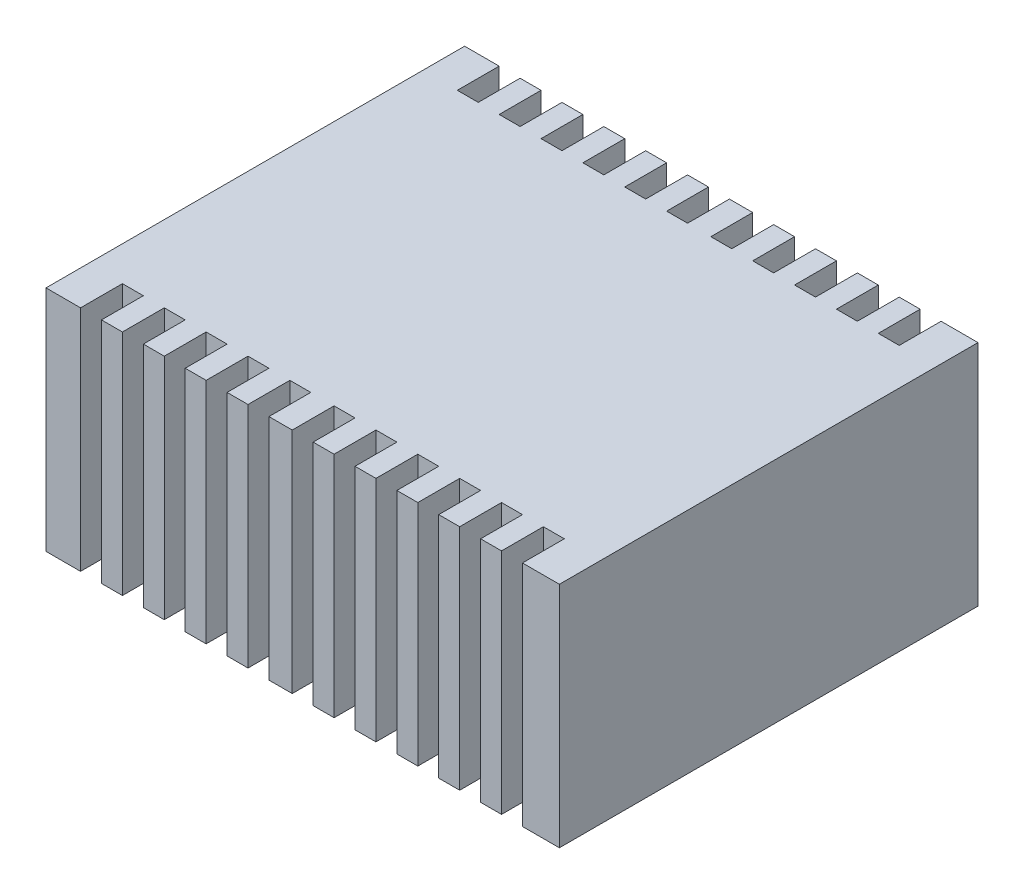
SolidWorks part; units mm, degrees
ref_plane "Front Plane" through (0, 0, 0) normal (0, 0, 1) x (1, 0, 0)
ref_plane "Top Plane" through (0, 0, 0) normal (0, 1, 0) x (1, 0, 0)
ref_plane "Right Plane" through (0, 0, 0) normal (1, 0, 0) x (0, 0, -1)
sketch "Sketch1" plane through (0, 0, 0) normal (0, 0, 1) x (1, 0, 0)
  line L0 (390.2862, -454.0022) -> (340.2862, -454.0022)
  line L1 (-347.891, 41.2406) -> (878.4633, 41.2406)
  line L2 (-347.891, 41.2406) -> (-347.891, -504.0022)
  line L3 (-347.891, -504.0022) -> (-265.3555, -504.0022)
  line L4 (878.4633, 41.2406) -> (878.4633, -504.0022)
  line L5 (340.2862, -454.0022) -> (340.2862, -504.0022)
  line L6 (290.2862, -454.0022) -> (240.2862, -454.0022)
  line L7 (240.2862, -454.0022) -> (240.2862, -504.0022)
  line L8 (290.2862, -454.0022) -> (290.2862, -504.0022)
  line L9 (390.2862, -454.0022) -> (390.2862, -504.0022)
  line L10 (490.2862, -454.0022) -> (440.2862, -454.0022)
  line L11 (440.2862, -454.0022) -> (440.2862, -504.0022)
  line L12 (490.2862, -454.0022) -> (490.2862, -504.0022)
  line L13 (590.2862, -454.0022) -> (540.2862, -454.0022)
  line L14 (540.2862, -454.0022) -> (540.2862, -504.0022)
  line L15 (690.2862, -454.0022) -> (690.2862, -504.0022)
  line L16 (590.2862, -454.0022) -> (590.2862, -504.0022)
  line L17 (690.2862, -454.0022) -> (640.2862, -454.0022)
  line L18 (640.2862, -454.0022) -> (640.2862, -504.0022)
  line L19 (184.6445, -454.0022) -> (134.6445, -454.0022)
  line L20 (790.2862, -454.0022) -> (740.2862, -454.0022)
  line L21 (740.2862, -454.0022) -> (740.2862, -504.0022)
  line L22 (-265.3555, -454.0022) -> (-265.3555, -504.0022)
  line L23 (184.6445, -454.0022) -> (184.6445, -504.0022)
  line L24 (790.2862, -454.0022) -> (790.2862, -504.0022)
  line L25 (84.6445, -454.0022) -> (34.6445, -454.0022)
  line L26 (84.6445, -454.0022) -> (84.6445, -504.0022)
  line L27 (-15.3555, -454.0022) -> (-15.3555, -504.0022)
  line L28 (134.6445, -454.0022) -> (134.6445, -504.0022)
  line L29 (-115.3555, -454.0022) -> (-115.3555, -504.0022)
  line L30 (34.6445, -454.0022) -> (34.6445, -504.0022)
  line L31 (-65.3555, -454.0022) -> (-65.3555, -504.0022)
  line L32 (-215.3555, -454.0022) -> (-265.3555, -454.0022)
  line L33 (-165.3555, -454.0022) -> (-165.3555, -504.0022)
  line L34 (-15.3555, -454.0022) -> (-65.3555, -454.0022)
  line L35 (-115.3555, -454.0022) -> (-165.3555, -454.0022)
  line L36 (-215.3555, -454.0022) -> (-215.3555, -504.0022)
  line L37 (-215.3555, -504.0022) -> (-165.3555, -504.0022)
  line L38 (-115.3555, -504.0022) -> (-65.3555, -504.0022)
  line L39 (-15.3555, -504.0022) -> (34.6445, -504.0022)
  line L40 (84.6445, -504.0022) -> (134.6445, -504.0022)
  line L41 (184.6445, -504.0022) -> (240.2862, -504.0022)
  line L42 (290.2862, -504.0022) -> (340.2862, -504.0022)
  line L43 (390.2862, -504.0022) -> (440.2862, -504.0022)
  line L44 (490.2862, -504.0022) -> (540.2862, -504.0022)
  line L45 (690.2862, -504.0022) -> (740.2862, -504.0022)
  line L46 (790.2862, -504.0022) -> (878.4633, -504.0022)
  line L47 (590.2862, -504.0022) -> (640.2862, -504.0022)
extrude "Boss-Extrude1" add sketch "Sketch1" along normal blind 1000
sketch "Sketch2" plane through (0, 0, 1000) normal (0, 0, 1) x (1, 0, 0)
  line L0 (-265.3555, -454.0022) -> (-265.3555, 201.7073)
  line L1 (-215.3555, 201.7073) -> (-165.3555, 201.7073)
  line L2 (-215.3555, 201.7073) -> (-215.3555, -454.0022)
  line L3 (-215.3555, -454.0022) -> (-265.3555, -454.0022)
  line L4 (-165.3555, 201.7073) -> (-165.3555, -454.0022)
  line L5 (-165.3555, -454.0022) -> (-115.3555, -454.0022)
  line L6 (-115.3555, -454.0022) -> (-115.3555, 201.7073)
  line L7 (-115.3555, 201.7073) -> (-65.3555, 201.7073)
  line L8 (-65.3555, 201.7073) -> (-65.3555, -454.0022)
  line L9 (-65.3555, -454.0022) -> (-15.3555, -454.0022)
  line L10 (-15.3555, -454.0022) -> (-15.3555, 201.7073)
  line L11 (-15.3555, 201.7073) -> (34.6445, 201.7073)
  line L12 (34.6445, 201.7073) -> (34.6445, -454.0022)
  line L13 (34.6445, -454.0022) -> (84.6445, -454.0022)
  line L14 (84.6445, -454.0022) -> (84.6445, 201.7073)
  line L15 (84.6445, 201.7073) -> (134.6445, 201.7073)
  line L16 (134.6445, 201.7073) -> (134.6445, -454.0022)
  line L17 (134.6445, -454.0022) -> (184.6445, -454.0022)
  line L18 (184.6445, -454.0022) -> (184.6445, 201.7073)
  line L19 (184.6445, 201.7073) -> (240.2862, 201.7073)
  line L20 (240.2862, 201.7073) -> (240.2862, -454.0022)
  line L21 (240.2862, -454.0022) -> (290.2862, -454.0022)
  line L22 (290.2862, -454.0022) -> (290.2862, 201.7073)
  line L23 (290.2862, 201.7073) -> (340.2862, 201.7073)
  line L24 (340.2862, 201.7073) -> (340.2862, -454.0022)
  line L25 (340.2862, -454.0022) -> (390.2862, -454.0022)
  line L26 (390.2862, -454.0022) -> (390.2862, 201.7073)
  line L27 (390.2862, 201.7073) -> (440.2862, 201.7073)
  line L28 (440.2862, 201.7073) -> (440.2862, -454.0022)
  line L29 (440.2862, -454.0022) -> (490.2862, -454.0022)
  line L30 (490.2862, -454.0022) -> (490.2862, 201.7073)
  line L31 (490.2862, 201.7073) -> (540.2862, 201.7073)
  line L32 (540.2862, 201.7073) -> (540.2862, -454.0022)
  line L33 (540.2862, -454.0022) -> (590.2862, -454.0022)
  line L34 (590.2862, -454.0022) -> (590.2862, 201.7073)
  line L35 (590.2862, 201.7073) -> (640.2862, 201.7073)
  line L36 (640.2862, 201.7073) -> (640.2862, -454.0022)
  line L37 (640.2862, -454.0022) -> (690.2862, -454.0022)
  line L38 (690.2862, -454.0022) -> (690.2862, 201.7073)
  line L39 (690.2862, 201.7073) -> (740.2862, 201.7073)
  line L40 (740.2862, 201.7073) -> (740.2862, -454.0022)
  line L41 (740.2862, -454.0022) -> (790.2862, -454.0022)
  line L42 (790.2862, -454.0022) -> (790.2862, 367.4342)
  line L43 (790.2862, 367.4342) -> (-265.3555, 367.4342)
  line L44 (-265.3555, 367.4342) -> (-265.3555, 201.7073)
  line L45 (790.2862, -454.0022) -> (1744.499, -200.374) construction
extrude "Cut-Extrude1" cut sketch "Sketch2" against normal blind 100
sketch "Sketch3" plane through (0, 0, 0) normal (0, 0, -1) x (-1, 0, 0)
  line L0 (-790.2862, -454.0022) -> (-790.2862, 201.7073)
  line L1 (-740.2862, 201.7073) -> (-690.2862, 201.7073)
  line L2 (-740.2862, 201.7073) -> (-740.2862, -454.0022)
  line L3 (-740.2862, -454.0022) -> (-790.2862, -454.0022)
  line L4 (-690.2862, 201.7073) -> (-690.2862, -454.0022)
  line L5 (-690.2862, -454.0022) -> (-640.2862, -454.0022)
  line L6 (-640.2862, -454.0022) -> (-640.2862, 201.7073)
  line L7 (-640.2862, 201.7073) -> (-590.2862, 201.7073)
  line L8 (-590.2862, 201.7073) -> (-590.2862, -454.0022)
  line L9 (-590.2862, -454.0022) -> (-540.2862, -454.0022)
  line L10 (-540.2862, -454.0022) -> (-540.2862, 201.7073)
  line L11 (-540.2862, 201.7073) -> (-490.2862, 201.7073)
  line L12 (-490.2862, 201.7073) -> (-490.2862, -454.0022)
  line L13 (-490.2862, -454.0022) -> (-440.2862, -454.0022)
  line L14 (-440.2862, -454.0022) -> (-440.2862, 201.7073)
  line L15 (-440.2862, 201.7073) -> (-390.2862, 201.7073)
  line L16 (-390.2862, 201.7073) -> (-390.2862, -454.0022)
  line L17 (-390.2862, -454.0022) -> (-340.2862, -454.0022)
  line L18 (-340.2862, -454.0022) -> (-340.2862, 201.7073)
  line L19 (-340.2862, 201.7073) -> (-284.6445, 201.7073)
  line L20 (-284.6445, 201.7073) -> (-284.6445, -454.0022)
  line L21 (-284.6445, -454.0022) -> (-234.6445, -454.0022)
  line L22 (-234.6445, -454.0022) -> (-234.6445, 201.7073)
  line L23 (-234.6445, 201.7073) -> (-184.6445, 201.7073)
  line L24 (-184.6445, 201.7073) -> (-184.6445, -454.0022)
  line L25 (-184.6445, -454.0022) -> (-134.6445, -454.0022)
  line L26 (-134.6445, -454.0022) -> (-134.6445, 201.7073)
  line L27 (-134.6445, 201.7073) -> (-84.6445, 201.7073)
  line L28 (-84.6445, 201.7073) -> (-84.6445, -454.0022)
  line L29 (-84.6445, -454.0022) -> (-34.6445, -454.0022)
  line L30 (-34.6445, -454.0022) -> (-34.6445, 201.7073)
  line L31 (-34.6445, 201.7073) -> (15.3555, 201.7073)
  line L32 (15.3555, 201.7073) -> (15.3555, -454.0022)
  line L33 (15.3555, -454.0022) -> (65.3555, -454.0022)
  line L34 (65.3555, -454.0022) -> (65.3555, 201.7073)
  line L35 (65.3555, 201.7073) -> (115.3555, 201.7073)
  line L36 (115.3555, 201.7073) -> (115.3555, -454.0022)
  line L37 (115.3555, -454.0022) -> (165.3555, -454.0022)
  line L38 (165.3555, -454.0022) -> (165.3555, 201.7073)
  line L39 (165.3555, 201.7073) -> (215.3555, 201.7073)
  line L40 (215.3555, 201.7073) -> (215.3555, -454.0022)
  line L41 (215.3555, -454.0022) -> (265.3555, -454.0022)
  line L42 (265.3555, -454.0022) -> (265.3555, 367.4342)
  line L43 (265.3555, 367.4342) -> (-790.2862, 367.4342)
  line L44 (-790.2862, 367.4342) -> (-790.2862, 201.7073)
extrude "Cut-Extrude2" cut sketch "Sketch3" against normal blind 100
